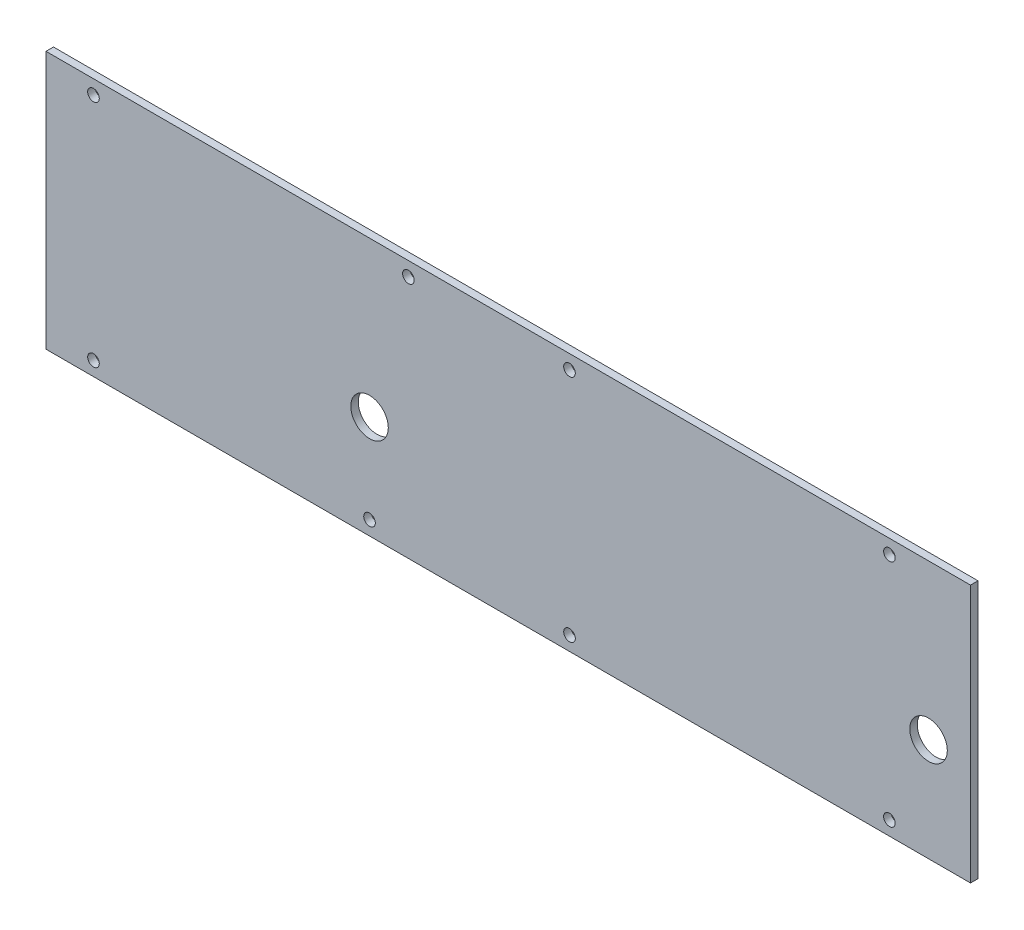
SolidWorks part; units mm, degrees
ref_plane "Front Plane" through (0, 0, 0) normal (0, 0, 1) x (1, 0, 0)
ref_plane "Top Plane" through (0, 0, 0) normal (0, 1, 0) x (1, 0, 0)
ref_plane "Right Plane" through (0, 0, 0) normal (1, 0, 0) x (0, 0, -1)
ref_plane "Plane1" through (0, 0, 1.1049) normal (0, 0, 1) x (1, 0, 0)
sketch "Sketch1" plane through (0, 0, 1.1049) normal (0, 0, 1) x (1, 0, 0)
  line L0 (-136.525, 38.1) -> (-136.525, -38.1)
  line L1 (-136.525, -38.1) -> (136.525, -38.1)
  line L2 (136.525, -38.1) -> (136.525, 38.1)
  line L3 (136.525, 38.1) -> (-136.525, 38.1)
extrude "Boss-Extrude1" add sketch "Sketch1" against normal blind 2.2098
hole_wizard "Hole1" positions "Sketch3" profile "Sketch2" legacy
sketch "Sketch3" plane through (0, 0, 1.1049) normal (0, 0, 1) x (1, 0, 0)
  point P0 (-40.9702, -33.9217)
  point P1 (18.0848, 33.9217)
  point P2 (-122.5042, -33.9217)
  point P3 (-122.5042, 33.9217)
  point P4 (-29.4894, 33.9217)
  point P5 (112.5728, 33.9217)
  point P6 (18.0848, -33.9217)
  point P7 (112.5728, -33.9217)
sketch "Sketch2" plane through (-40.9702, -33.9217, 1.1049) normal (1, 0, 0) x (0, -1, 0)
  line L0 (0, 0) -> (0, 2.2098)
  line L1 (0, 2.2098) -> (1.7145, 2.2098)
  line L2 (1.7145, 2.2098) -> (1.7145, 0)
  line L3 (1.7145, 0) -> (0, 0)
  line L4 (0, 110) -> (0, -10) construction
  dimension "Diameter" = 3.429
  dimension "Depth" = 2.2098
hole_wizard "Hole2" positions "Sketch5" profile "Sketch4" legacy
sketch "Sketch5" plane through (0, 0, 1.1049) normal (0, 0, 1) x (1, 0, 0)
  point P0 (-40.9702, -7.6581)
  point P1 (124.1298, -7.6581)
sketch "Sketch4" plane through (-40.9702, -7.6581, 1.1049) normal (1, 0, 0) x (0, -1, 0)
  line L0 (0, 0) -> (0, 2.2098)
  line L1 (0, 2.2098) -> (5.5372, 2.2098)
  line L2 (5.5372, 2.2098) -> (5.5372, 0)
  line L3 (5.5372, 0) -> (0, 0)
  line L4 (0, 110) -> (0, -10) construction
  dimension "Diameter" = 11.0744
  dimension "Depth" = 2.2098
